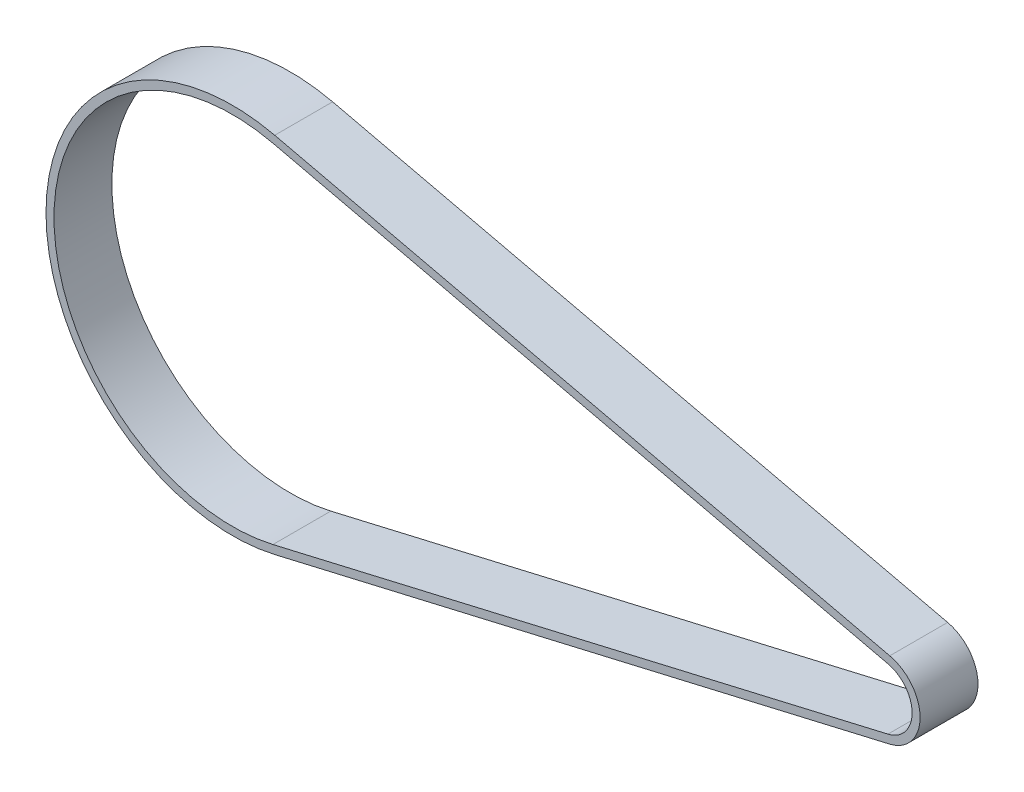
SolidWorks part; units mm, degrees
ref_plane "Front" through (0, 0, 0) normal (0, 0, 1) x (1, 0, 0)
ref_plane "Top" through (0, 0, 0) normal (0, 1, 0) x (1, 0, 0)
ref_plane "Right" through (0, 0, 0) normal (1, 0, 0) x (0, 0, -1)
sketch "Эскиз1" plane through (0, 0, 0) normal (0, 0, 1) x (1, 0, 0)
  line L0 (0, 0) -> (112, 0) construction
  line L1 (7.3082, 31.3612) -> (113.5394, 6.606)
  line L2 (113.5394, -6.606) -> (7.3082, -31.3612)
  line L3 (113.2262, -5.262) -> (6.995, -30.0172)
  line L4 (6.995, 30.0172) -> (113.2262, 5.262)
  arc A0 (7.3082, 31.3612) -> (7.3082, -31.3612) centre (0, 0) ccw
  arc A1 (113.5394, -6.606) -> (113.5394, 6.606) centre (112, 0) ccw
  arc A2 (6.995, 30.0172) -> (6.995, -30.0172) centre (0, 0) ccw
  arc A3 (113.2262, -5.262) -> (113.2262, 5.262) centre (112, 0) ccw
  dimension "D1" = 64.403
  dimension "D3" = 13.566
  dimension "D2" = 112
  dimension "D4" = 1.38
extrude "Бобышка-Вытянуть1" add sketch "Эскиз1" against normal blind 10
